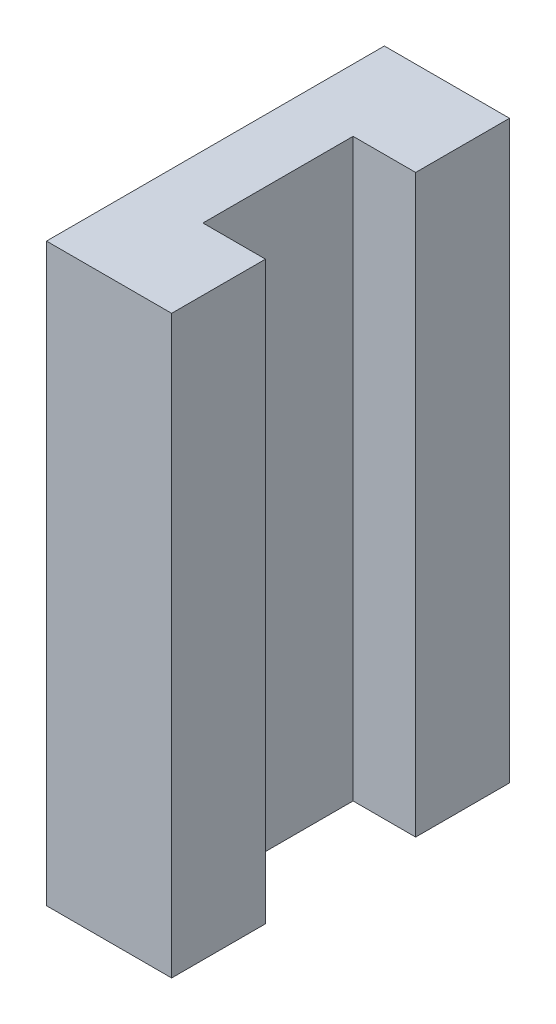
SolidWorks part; units mm, degrees
ref_plane "Front Plane" through (0, 0, 0) normal (0, 0, 1) x (1, 0, 0)
ref_plane "Top Plane" through (0, 0, 0) normal (0, 1, 0) x (1, 0, 0)
ref_plane "Right Plane" through (0, 0, 0) normal (1, 0, 0) x (0, 0, -1)
sketch "Sketch1" plane through (0, 0, 0) normal (0, 1, 0) x (1, 0, 0)
  line L0 (5, 6) -> (5, 13.5)
  line L1 (-5, -13.5) -> (5, -13.5)
  line L2 (-5, -13.5) -> (-5, 13.5)
  line L3 (-5, 13.5) -> (5, 13.5)
  line L4 (5, -13.5) -> (5, -6)
  line L5 (-5, -13.5) -> (5, 13.5) construction
  line L6 (-5, 13.5) -> (5, -13.5) construction
  line L7 (5, 6) -> (0, 6)
  line L9 (5, -6) -> (0, -6)
  line L10 (0, 6) -> (0, -6)
  point P0 (0, 0)
  point P10 (0, 0)
  dimension "D1" = 27
  dimension "D2" = 10
  dimension "D3" = 12
  dimension "D4" = 5
extrude "Boss-Extrude1" add sketch "Sketch1" along normal blind 46
sketch "Sketch2" plane through (-5, 0, 0) normal (-1, 0, 0) x (0, 0, 1)
  line L1 (-10, 13) -> (10, 13) construction
  line L2 (-10, 13) -> (-10, 33) construction
  line L3 (-10, 33) -> (10, 33) construction
  line L4 (10, 13) -> (10, 33) construction
  line L5 (-10, 13) -> (10, 33) construction
  line L6 (-10, 33) -> (10, 13) construction
  line L8 (-13.5, 46) -> (-13.5, 0) construction
  point P0 (0, 23)
  point P5 (0, 13)
  point P9 (-13.5, 23)
  point P10 (-10, 23)
  dimension "D1" = 20
hole_wizard "M3 Tapped Hole1" positions "Sketch3" profile "Sketch4" tap size "M3" standard "ISO"
sketch "Sketch3" plane through (-5, 0, 0) normal (-1, 0, 0) x (0, 0, 1)
  point P0 (10, 33)
  point P3 (-10, 33)
  point P6 (-10, 13)
  point P9 (10, 13)
sketch "Sketch4" plane through (-5, 33, 10) normal (0, 1, 0) x (0, 0, 1)
  line L0 (0, 0) -> (0, 8.2511)
  line L1 (0, 8.2511) -> (1.25, 7.5)
  line L2 (1.25, 7.5) -> (1.25, 0)
  line L5 (1.25, 0) -> (0, 0)
  line L10 (0, 8.2511) -> (-1.25, 7.5) construction
  line L11 (0, -6.35) -> (0, 107.95) construction
  dimension "Tap Drill Dia." = 2.5
  dimension "Tap Drill Depth" = 7.5
  dimension "Drill Angle" = 118
cosmetic thread "Hole Thread1" parameters "D1"=6, "D2"=3
cosmetic thread "Hole Thread2" parameters "D1"=6, "D2"=3
cosmetic thread "Hole Thread3" parameters "D1"=6, "D2"=3
cosmetic thread "Hole Thread4" parameters "D1"=6, "D2"=3
